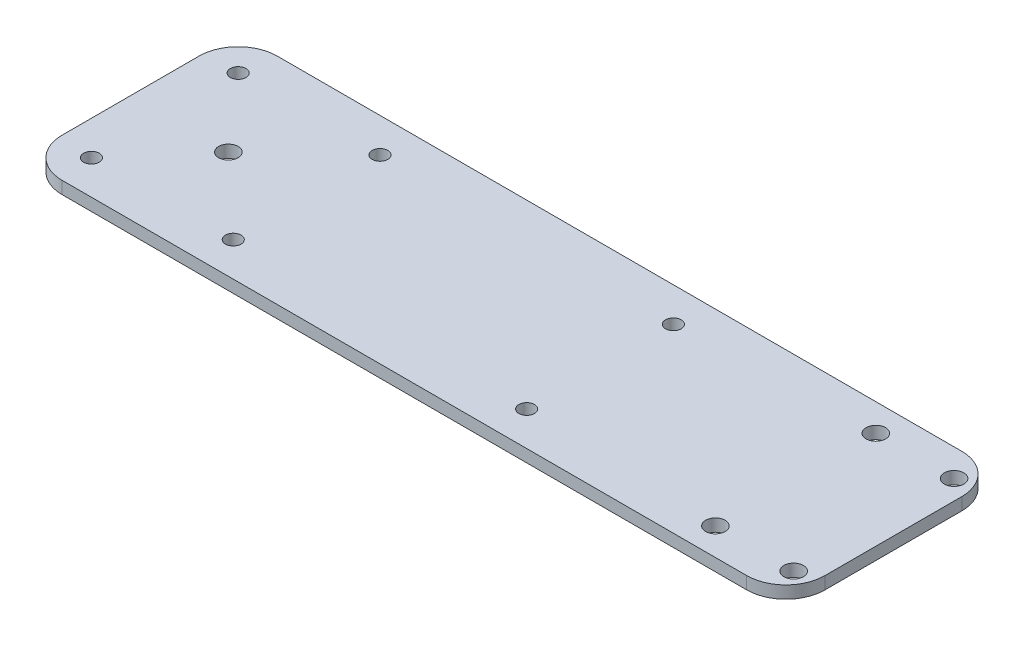
SolidWorks part; units mm, degrees
ref_plane "Front Plane" through (0, 0, 0) normal (0, 0, 1) x (1, 0, 0)
ref_plane "Top Plane" through (0, 0, 0) normal (0, 1, 0) x (1, 0, 0)
ref_plane "Right Plane" through (0, 0, 0) normal (1, 0, 0) x (0, 0, -1)
sketch "Sketch1" plane through (0, 0, 0) normal (0, 1, 0) x (1, 0, 0)
  line L0 (-25, 0) -> (0, 0) construction
  line L1 (-25, 27.5) -> (170, 27.5)
  line L2 (-25, 27.5) -> (-25, -27.5)
  line L3 (-25, -27.5) -> (170, -27.5)
  line L4 (170, 27.5) -> (170, -27.5)
  point P7 (150, 0)
  dimension "D1" = 55
  dimension "D2" = 150
  dimension "D3" = 20
  dimension "D4" = 25
extrude "Boss-Extrude1" add sketch "Sketch1" along normal blind 3.175
fillet "Fillet1" radius 10 4 edges at (-25, 1.5875, 27.5) (-25, 1.5875, -27.5) (170, 1.5875, -27.5) (170, 1.5875, 27.5)
hole_wizard "Ø5.0mm Dowel Hole1" positions "Sketch3" profile "Sketch4" hole size "Ø5.0" standard "DIN" end condition up to next
sketch "Sketch3" plane through (0, 3.175, 0) normal (0, 1, 0) x (1, 0, 0)
  point P0 (0, 0)
sketch "Sketch4" plane through (0, 3.175, 0) normal (1, 0, 0) x (0, 0, 1)
  line L0 (0, 0) -> (0, 3.175)
  line L1 (0, 3.175) -> (2.5, 3.175)
  line L2 (2.5, 3.175) -> (2.5, 0)
  line L5 (2.5, 0) -> (0, 0)
  line L11 (0, -6.35) -> (0, 107.95) construction
  dimension "Thru Hole Dia." = 5
  dimension "Thru Hole Depth" = 3.175
hole_wizard "Ø4.0mm Dowel Hole1" positions "Sketch5" profile "Sketch6" hole size "Ø4.0" standard "DIN" end condition up to next
sketch "Sketch5" plane through (0, 3.175, 0) normal (0, 1, 0) x (1, 0, 0)
  line L0 (-25, 17.5) -> (-25, -17.5) construction
  line L1 (-15, -27.5) -> (160, -27.5) construction
  line L2 (20, -18.75) -> (95, -18.75) construction
  line L3 (-25, 0) -> (170, 0) construction
  line L4 (170, -17.5) -> (170, 17.5) construction
  circle A0 centre (0, 0) radius 2.5 construction
  point P0 (-16.25, -18.75)
  point P2 (20, -18.75)
  point P16 (95, -18.75)
  point P27 (95, 18.75)
  point P28 (20, 18.75)
  point P29 (-16.25, 18.75)
  dimension "D3" = 20
  dimension "D1" = 8.75
  dimension "D2" = 8.75
  dimension "D5" = 75
  dimension "D4" = 2
sketch "Sketch6" plane through (-16.25, 3.175, 18.75) normal (1, 0, 0) x (0, 0, 1)
  line L0 (0, 0) -> (0, 3.175)
  line L1 (0, 3.175) -> (2, 3.175)
  line L2 (2, 3.175) -> (2, 0)
  line L5 (2, 0) -> (0, 0)
  line L11 (0, -6.35) -> (0, 107.95) construction
  dimension "Thru Hole Dia." = 4
  dimension "Thru Hole Depth" = 3.175
hole_wizard "Ø5.0mm Dowel Hole2" positions "Sketch7" profile "Sketch8" hole size "Ø5.0" standard "DIN" end condition through all
sketch "Sketch7" plane through (0, 3.175, 0) normal (0, 1, 0) x (1, 0, 0)
  line L0 (155, 27.5) -> (155, -27.5) construction
  line L1 (160, 27.5) -> (-15, 27.5) construction
  line L2 (-15, -27.5) -> (160, -27.5) construction
  line L4 (170, 0) -> (-25, 0) construction
  line L5 (170, -17.5) -> (170, 17.5) construction
  line L6 (-25, 17.5) -> (-25, -17.5) construction
  point P0 (165, 20.5)
  point P19 (145, 20.5)
  point P20 (165, -20.5)
  point P21 (145, -20.5)
  dimension "D1" = 15
  dimension "D2" = 7
  dimension "D3" = 5
sketch "Sketch8" plane through (165, 3.175, -20.5) normal (1, 0, 0) x (0, 0, 1)
  line L0 (0, 0) -> (0, 3.175)
  line L1 (0, 3.175) -> (2.5, 3.175)
  line L2 (2.5, 3.175) -> (2.5, 0)
  line L5 (2.5, 0) -> (0, 0)
  line L11 (0, -6.35) -> (0, 107.95) construction
  dimension "Thru Hole Dia." = 5
  dimension "Thru Hole Depth" = 3.175
equation "\"Pivot to Pivot Distance\"= 150mm"
equation "\"D2@Sketch1\"=\"Pivot to Pivot Distance\""
equation "\"Plate Thickness\"= 0.125in"
equation "\"D1@Boss-Extrude1\"=\"Plate Thickness\""
